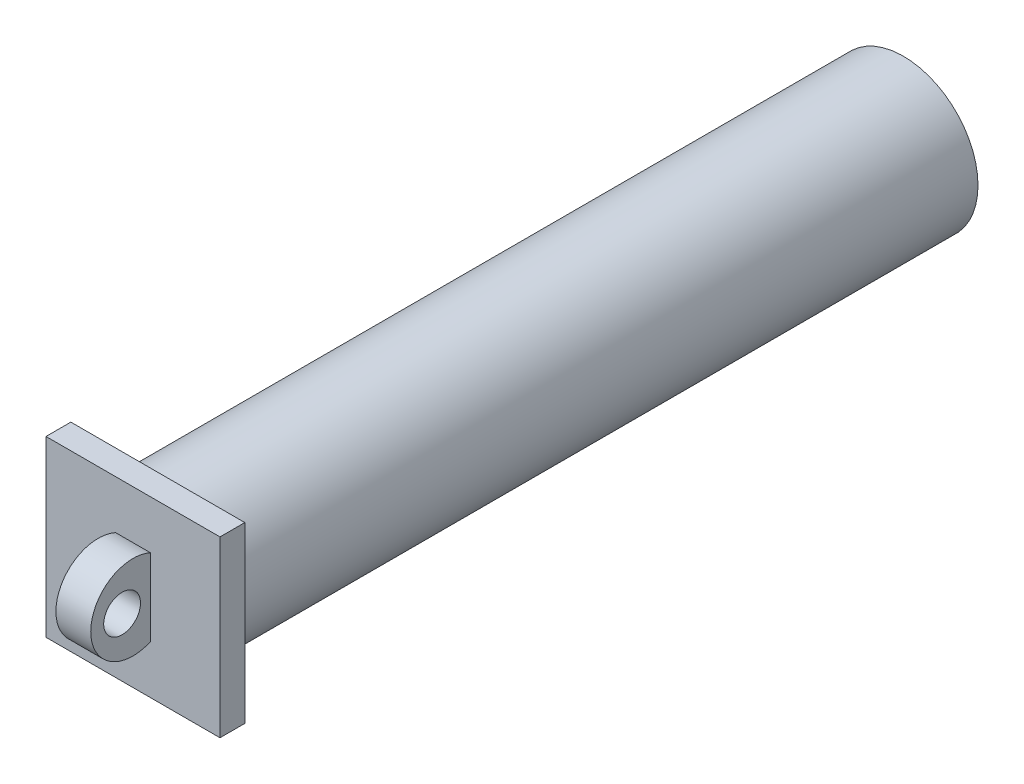
SolidWorks part; units mm, degrees
ref_plane "Front Plane" through (0, 0, 0) normal (0, 0, 1) x (1, 0, 0)
ref_plane "Top Plane" through (0, 0, 0) normal (0, 1, 0) x (1, 0, 0)
ref_plane "Right Plane" through (0, 0, 0) normal (1, 0, 0) x (0, 0, -1)
sketch "Sketch1" plane through (0, 0, 0) normal (0, 0, 1) x (1, 0, 0)
  circle A0 centre (0, 0) radius 15
  circle A1 centre (0, 0) radius 10
  dimension "D1" = 30
  dimension "D2" = 20
extrude "Boss-Extrude1" add sketch "Sketch1" along normal blind 150
sketch "Sketch2" plane through (0, 0, 150) normal (0, 0, 1) x (1, 0, 0)
  line L1 (-17.5, -17.5) -> (17.5, -17.5)
  line L2 (-17.5, -17.5) -> (-17.5, 17.5)
  line L3 (-17.5, 17.5) -> (17.5, 17.5)
  line L4 (17.5, -17.5) -> (17.5, 17.5)
  line L5 (-17.5, -17.5) -> (17.5, 17.5) construction
  line L6 (-17.5, 17.5) -> (17.5, -17.5) construction
  point P0 (0, 0)
  dimension "D1" = 35
  dimension "D2" = 35
extrude "Boss-Extrude2" add sketch "Sketch2" along normal blind 5
sketch "Sketch3" plane through (0, 0, 0) normal (1, 0, 0) x (0, 0, -1)
  line L1 (-155, -15) -> (-155, 15)
  line L2 (-150, -17.5) -> (-150, 17.5) construction
  line L3 (-150, -17.5) -> (-150, 17.5)
  circle A0 centre (-158.5, 0) radius 8.5
  point P6 (-158.4041, 0)
  point P7 (-150, 0)
  dimension "D1" = 17
extrude "Boss-Extrude3" add sketch "Sketch3" along normal mid plane 35 contours L1 A0
ref_plane "Plane1" through (3.5, 0, 0) normal (1, 0, 0) x (0, 0, -1)
sketch "Sketch5" plane through (3.5, 0, 0) normal (1, 0, 0) x (0, 0, -1)
  line L0 (-155, 7.746) -> (-155, -7.746)
  circle A0 centre (-158.5, 0) radius 8.5
extrude "Cut-Extrude2" cut sketch "Sketch5" along normal up to next contours L0 A0
ref_plane "Plane2" through (-3.5, 0, 0) normal (1, 0, 0) x (0, 0, -1)
sketch "Sketch6" plane through (-3.5, 0, 0) normal (1, 0, 0) x (0, 0, -1)
  line L0 (-155, 7.746) -> (-155, -7.746)
  circle A0 centre (-158.5, 0) radius 8.5
extrude "Cut-Extrude3" cut sketch "Sketch6" against normal up to next contours L0 A0
sketch "Sketch8" plane through (3.5, 0, 0) normal (1, 0, 0) x (0, 0, -1)
  circle A0 centre (-160.6901, 0) radius 3.7002
extrude "Cut-Extrude4" cut sketch "Sketch8" against normal through all
